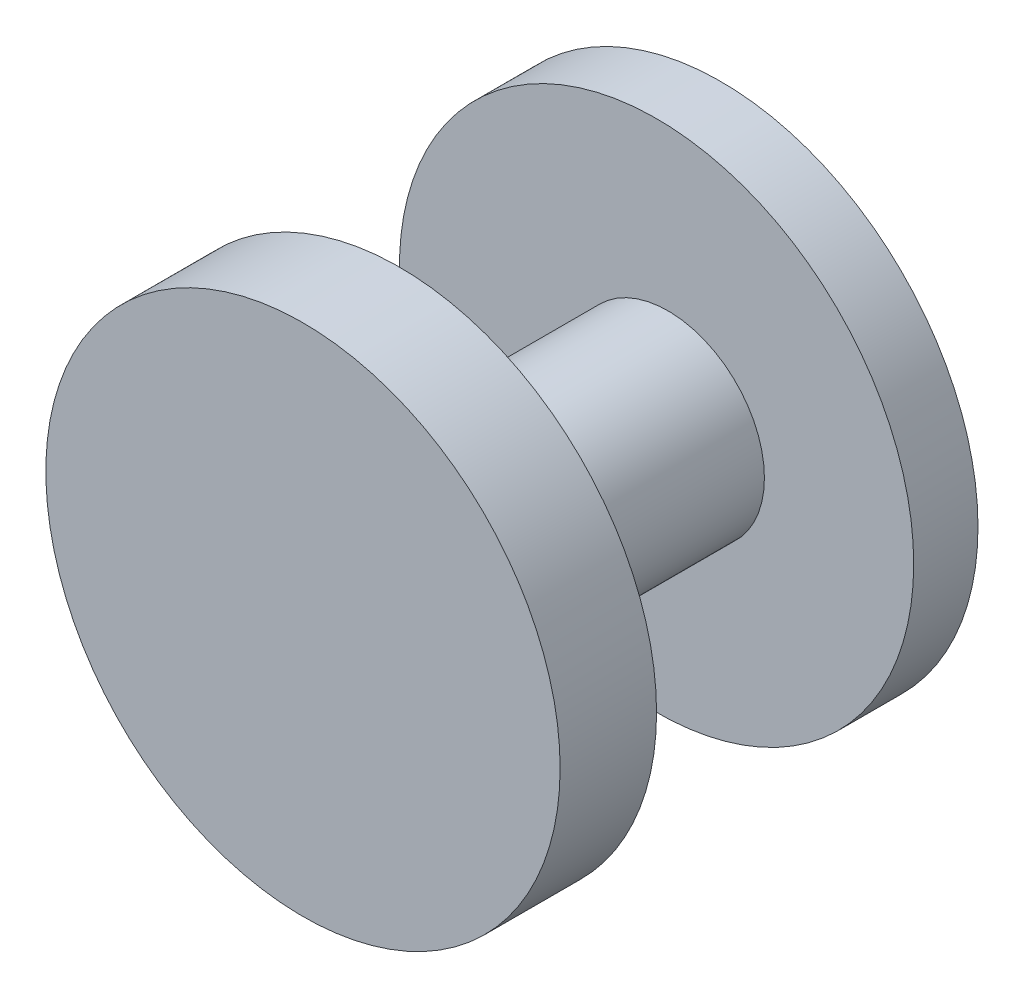
SolidWorks part; units mm, degrees
ref_plane "前视" through (0, 0, 0) normal (0, 0, 1) x (1, 0, 0)
ref_plane "上视" through (0, 0, 0) normal (0, 1, 0) x (1, 0, 0)
ref_plane "右视" through (0, 0, 0) normal (1, 0, 0) x (0, 0, -1)
sketch "草图1" plane through (0, 0, 0) normal (0, 0, 1) x (1, 0, 0)
  circle A0 centre (0, 0) radius 8
  dimension "D1" = 16
extrude "凸台-拉伸1" add sketch "草图1" along normal blind 2
sketch "草图2" plane through (0, 0, 0) normal (0, 0, -1) x (-1, 0, 0)
  circle A0 centre (0, 0) radius 2.5
  dimension "D1" = 5
extrude "凸台-拉伸2" add sketch "草图2" along normal blind 1
sketch "草图3" plane through (0, 0, 2) normal (0, 0, 1) x (1, 0, 0)
  circle A0 centre (0.3553, 0) radius 3
  dimension "D1" = 6
extrude "凸台-拉伸3" add sketch "草图3" along normal blind 8
sketch "草图4" plane through (0, 0, 10) normal (0, 0, 1) x (1, 0, 0)
  circle A0 centre (0, 0) radius 8
  dimension "D1" = 16
extrude "凸台-拉伸4" add sketch "草图4" along normal blind 3
